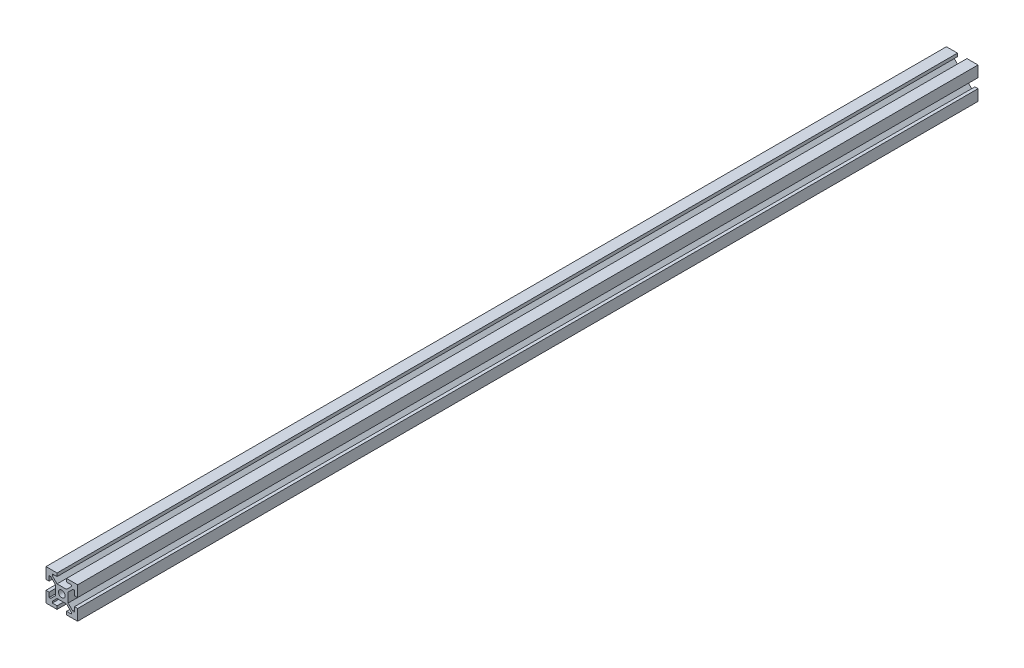
SolidWorks part; units mm, degrees
ref_plane "正面" through (0, 0, 0) normal (0, 0, 1) x (1, 0, 0)
ref_plane "平面" through (0, 0, 0) normal (0, 1, 0) x (1, 0, 0)
ref_plane "右側面" through (0, 0, 0) normal (1, 0, 0) x (0, 0, -1)
sketch "ｽｹｯﾁ2" plane through (0, 0, 0) normal (0, 0, 1) x (1, 0, 0)
  line L0 (0, 0) -> (0, 10) construction
  line L1 (-10, -10) -> (10, -10) construction
  line L2 (-10, -10) -> (-10, 10) construction
  line L3 (-10, 10) -> (10, 10) construction
  line L4 (10, -10) -> (10, 10) construction
  line L5 (-10, -10) -> (10, 10) construction
  line L6 (-10, 10) -> (10, -10) construction
  line L8 (3, 4) -> (-3, 4)
  line L9 (-6, 7) -> (6, 7) construction
  line L10 (-6, 8) -> (-6, 7)
  line L11 (6, 8) -> (6, 7)
  line L12 (-6, 7) -> (-3, 4)
  line L13 (3, 4) -> (6, 7)
  line L14 (-6, 8) -> (-3, 8)
  line L15 (-3, 8) -> (-3, 10)
  line L16 (-3, 10) -> (-10, 10)
  line L17 (6, 8) -> (3, 8)
  line L18 (3, 8) -> (3, 10)
  line L19 (3, 10) -> (10, 10)
  line L20 (7, 6) -> (4, 3)
  line L21 (4, -3) -> (4, 3)
  line L22 (4, -3) -> (7, -6)
  line L23 (8, -6) -> (8, -3)
  line L24 (8, -6) -> (7, -6)
  line L25 (8, -3) -> (10, -3)
  line L26 (10, -3) -> (10, -10)
  line L27 (8, 3) -> (10, 3)
  line L28 (10, 3) -> (10, 10)
  line L29 (8, 6) -> (8, 3)
  line L30 (8, 6) -> (7, 6)
  line L31 (6, -7) -> (3, -4)
  line L32 (-3, -4) -> (3, -4)
  line L33 (-3, -4) -> (-6, -7)
  line L34 (-6, -8) -> (-3, -8)
  line L35 (-6, -8) -> (-6, -7)
  line L36 (-3, -8) -> (-3, -10)
  line L37 (-3, -10) -> (-10, -10)
  line L38 (3, -8) -> (3, -10)
  line L39 (3, -10) -> (10, -10)
  line L40 (6, -8) -> (3, -8)
  line L41 (6, -8) -> (6, -7)
  line L42 (-7, -6) -> (-4, -3)
  line L43 (-4, 3) -> (-4, -3)
  line L44 (-4, 3) -> (-7, 6)
  line L45 (-8, 6) -> (-8, 3)
  line L46 (-8, 6) -> (-7, 6)
  line L47 (-8, 3) -> (-10, 3)
  line L48 (-10, 3) -> (-10, 10)
  line L49 (-8, -3) -> (-10, -3)
  line L50 (-10, -3) -> (-10, -10)
  line L51 (-8, -6) -> (-8, -3)
  line L52 (-8, -6) -> (-7, -6)
  circle A0 centre (0, 0) radius 2.1
  point P0 (0, 0)
  point P11 (0, 10)
  point P14 (0, 4)
  point P17 (0, 7)
  dimension "D8" = 4.2
  dimension "D1" = 20
  dimension "D2" = 6
  dimension "D3" = 2
  dimension "D4" = 4
  dimension "D5" = 12
  dimension "D6" = 6
  dimension "D7" = 4
extrude "ﾎﾞｽ - 押し出し1" add sketch "ｽｹｯﾁ2" along normal blind 570
